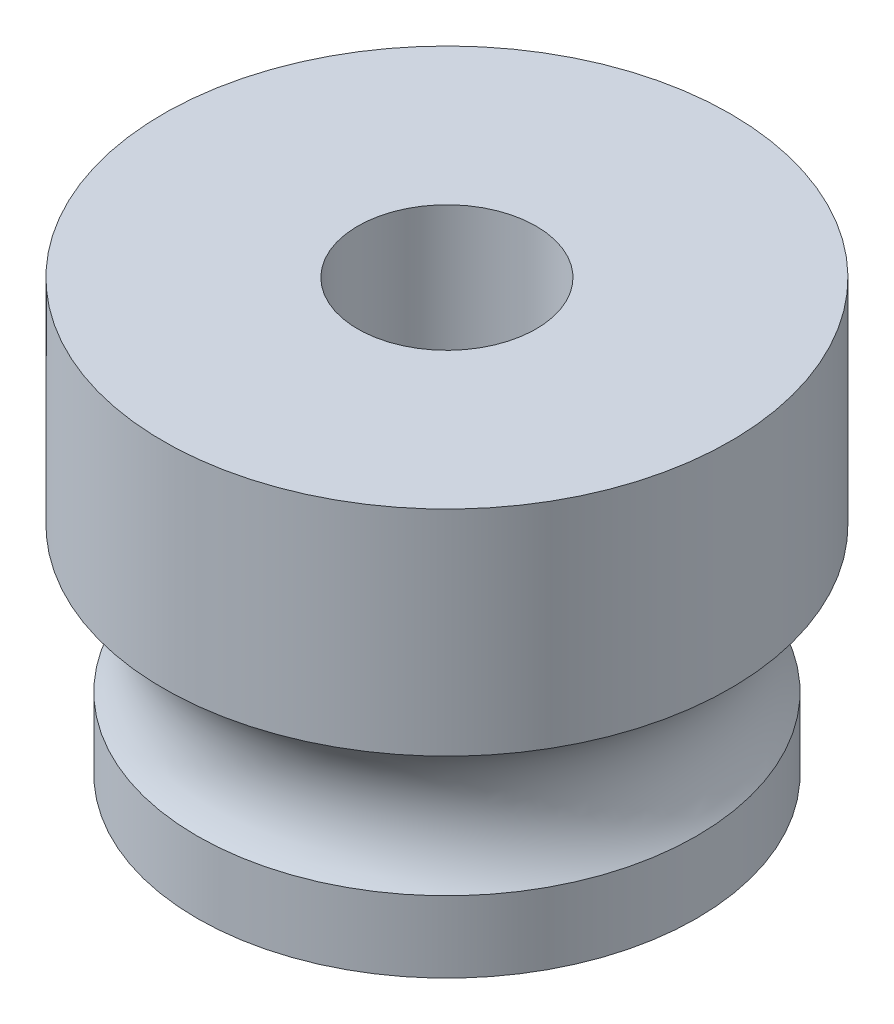
SolidWorks part; units mm, degrees
ref_plane "Piano frontale" through (0, 0, 0) normal (0, 0, 1) x (1, 0, 0)
ref_plane "Piano superiore" through (0, 0, 0) normal (0, 1, 0) x (1, 0, 0)
ref_plane "Piano destro" through (0, 0, 0) normal (1, 0, 0) x (0, 0, -1)
sketch "Schizzo1" plane through (0, 0, 0) normal (0, 0, 1) x (1, 0, 0)
  line L0 (0, -9.6439) -> (0, 27.1677) construction
  line L1 (0, 0) -> (3.5, 0)
  line L2 (3.5, 0) -> (3.5, 1)
  line L3 (0, 6.03) -> (3.975, 6.03)
  line L4 (3.975, 6.03) -> (3.975, 3.03)
  circle A0 centre (4.5, 1.8366) radius 1.3038
  dimension "D1" = 6.03
  dimension "D2" = 3
  dimension "D3" = 1
  dimension "D4" = 3.975
  dimension "D5" = 3.5
  dimension "D6" = 1
revolve "Rivoluzione1" add sketch "Schizzo1" angle 360 about L0
hole_wizard "Foro filettato M3x0.5-1" positions "Schizzo3" profile "Schizzo2" tap size "M3x0.5" standard "Ansi Metric" end condition through all
sketch "Schizzo3" plane through (0, 0, 0) normal (0, -1, 0) x (-1, 0, 0)
  point P0 (0, 0)
sketch "Schizzo2" plane through (0, 0, 0) normal (1, 0, 0) x (0, 0, -1)
  line L0 (0, 0) -> (0, 6.03)
  line L1 (0, 6.03) -> (1.25, 6.03)
  line L2 (1.25, 6.03) -> (1.25, 0)
  line L5 (1.25, 0) -> (0, 0)
  line L11 (0, -6.35) -> (0, 107.95) construction
  dimension "Thru Tap Drill Dia." = 2.5
  dimension "Thru Tap Drill Depth" = 6.03
cosmetic thread "Filettatura del foro1" parameters "D2"=3
